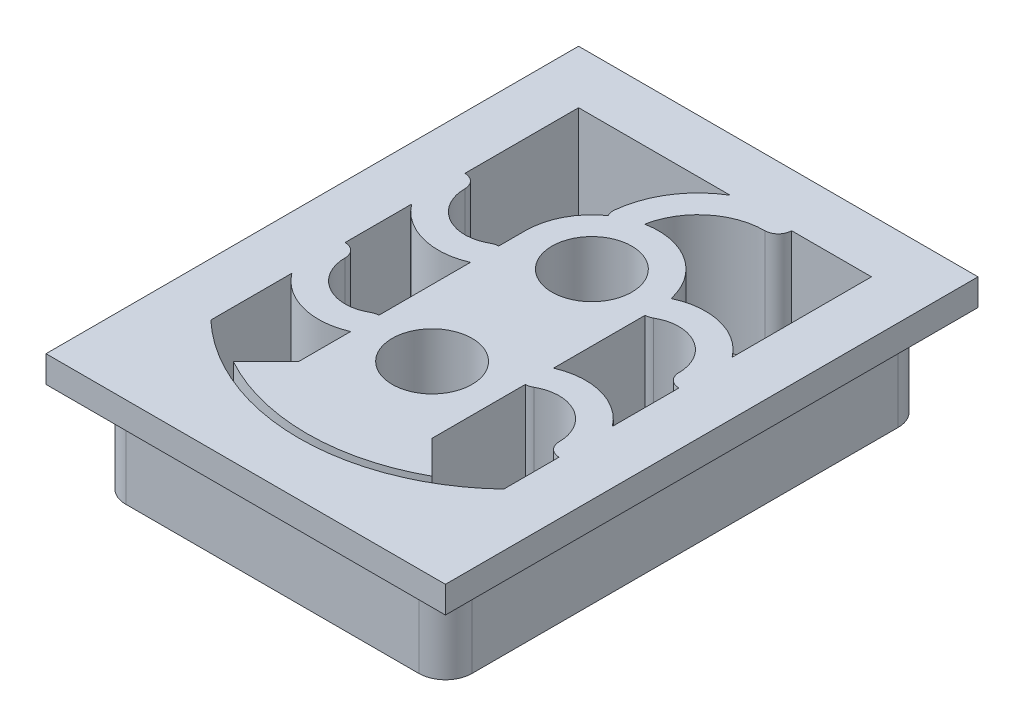
SolidWorks part; units mm, degrees
ref_plane "Front Plane" through (0, 0, 0) normal (0, 0, 1) x (1, 0, 0)
ref_plane "Top Plane" through (0, 0, 0) normal (0, 1, 0) x (1, 0, 0)
ref_plane "Right Plane" through (0, 0, 0) normal (1, 0, 0) x (0, 0, -1)
sketch "Sketch1" plane through (0, 0, 0) normal (0, 1, 0) x (1, 0, 0)
  line L1 (-6.5, -9) -> (6.5, -9)
  line L2 (-6.5, -9) -> (-6.5, 9)
  line L3 (-6.5, 9) -> (6.5, 9)
  line L4 (6.5, -9) -> (6.5, 9)
  line L5 (-6.5, -9) -> (6.5, 9) construction
  line L6 (-6.5, 9) -> (6.5, -9) construction
  point P0 (0, 0)
  dimension "D1" = 18
  dimension "D2" = 13
extrude "Boss-Extrude1" add sketch "Sketch1" along normal blind 3.4
sketch "Sketch2" plane through (0, 3.4, 0) normal (0, 1, 0) x (1, 0, 0)
  line L8 (7.5, -10) -> (7.5, 10)
  line L9 (7.5, 10) -> (-7.5, 10)
  line L10 (-7.5, 10) -> (-7.5, -10)
  line L11 (-7.5, -10) -> (7.5, -10)
  line L12 (7.5, -10) -> (7.5, 10)
  line L13 (7.5, 10) -> (-7.5, 10)
  line L14 (-7.5, 10) -> (-7.5, -10)
  line L15 (-7.5, -10) -> (7.5, -10)
  dimension "D1" = 1
extrude "Boss-Extrude2" add sketch "Sketch2" along normal blind 1
sketch "Sketch4" plane through (0, 0, 0) normal (0, -1, 0) x (1, 0, 0)
  line L0 (-3.734, 6.734) -> (-2.5, 5.5)
  line L1 (3.734, 6.734) -> (2.5, 5.5)
  line L4 (0, -3) -> (0, 3)
  line L6 (2.5, -5.5) -> (-2.5, -5.5)
  line L7 (2.5, -5.5) -> (2.5, 5.5)
  line L8 (5.5, -8) -> (5.5, 8)
  line L9 (5.5, 8) -> (-5.5, 8)
  line L10 (-5.5, 8) -> (-5.5, -8)
  line L11 (-5.5, -8) -> (5.5, -8)
  line L12 (5.5, -8) -> (5.5, 8)
  line L13 (5.5, 8) -> (-5.5, 8)
  line L14 (-5.5, 8) -> (-5.5, -8)
  line L15 (-5.5, -8) -> (5.5, -8)
  line L16 (2.5, 5.5) -> (-2.5, 5.5)
  line L17 (-2.5, -5.5) -> (-2.5, 5.5)
  line L18 (2.5, -5.5) -> (-2.5, 5.5) construction
  line L19 (2.5, 5.5) -> (-2.5, -5.5) construction
  circle A0 centre (0, 3) radius 1.5
  circle A1 centre (0, -3) radius 1.5
  circle A3 centre (0, -3) radius 2.5
  arc A4 (-2.5, 3) -> (-5.5, 1.2679) centre (-3.5, 1.2679) ccw
  arc A5 (2.5, 1.5) -> (5.5, 3.2321) centre (3.5, 3.2321) ccw
  arc A6 (2.5, -3) -> (5.5, -1.2679) centre (3.5, -1.2679) ccw
  arc A7 (-2.5, -1.5) -> (-5.5, -3.2321) centre (-3.5, -3.2321) ccw
  arc A9 (-1, -5.2913) -> (2, -8) centre (2, -4.9843) ccw
  arc A11 (3.734, 6.734) -> (-3.734, 6.734) centre (0, 0) ccw
  arc A12 (0, 8) -> (-5.5, 5.8095) centre (0, 0) ccw
  arc A13 (0, 8) -> (5.5, 5.8095) centre (0, 0) cw
  arc A14 (-2.25, -1.067) -> (-6, -3.2321) centre (-3.5, -3.2321) ccw
  arc A15 (-2.25, 3.433) -> (-6, 1.2679) centre (-3.5, 1.2679) ccw
  arc A16 (2.25, 1.067) -> (6, 3.2321) centre (3.5, 3.2321) ccw
  arc A17 (2.25, -3.433) -> (6, -1.2679) centre (3.5, -1.2679) ccw
  arc A18 (-2.75, -1.933) -> (-5, -3.2321) centre (-3.5, -3.2321) ccw
  arc A19 (-2.75, 2.567) -> (-5, 1.2679) centre (-3.5, 1.2679) ccw
  arc A20 (2.75, 1.933) -> (5, 3.2321) centre (3.5, 3.2321) ccw
  arc A21 (2.75, -2.567) -> (5, -1.2679) centre (3.5, -1.2679) ccw
  arc A22 (-2.25, -1.067) -> (-2.75, -1.933) centre (-2.5, -1.5) cw
  arc A23 (-6, -3.2321) -> (-5, -3.2321) centre (-5.5, -3.2321) ccw
  arc A24 (-2.25, 3.433) -> (-2.75, 2.567) centre (-2.5, 3) cw
  arc A25 (-6, 1.2679) -> (-5, 1.2679) centre (-5.5, 1.2679) ccw
  arc A26 (2.25, 1.067) -> (2.75, 1.933) centre (2.5, 1.5) cw
  arc A27 (6, 3.2321) -> (5, 3.2321) centre (5.5, 3.2321) ccw
  arc A28 (2.25, -3.433) -> (2.75, -2.567) centre (2.5, -3) cw
  arc A29 (6, -1.2679) -> (5, -1.2679) centre (5.5, -1.2679) ccw
  arc A31 (-1.4974, -5.3422) -> (2, -8.5) centre (2, -4.9843) ccw
  arc A33 (-0.5026, -5.2404) -> (2, -7.5) centre (2, -4.9843) ccw
  arc A36 (-1.4974, -5.3422) -> (-0.5026, -5.2404) centre (-1, -5.2913) cw
  arc A37 (2, -8.5) -> (2, -7.5) centre (2, -8) ccw
  point P3 (0, 0)
  point P5 (0, 0)
  dimension "D3" = 3
  dimension "D6" = 7.7
  dimension "D8" = 4.5
  dimension "D7" = 2
  dimension "D13" = 135
  dimension "D14" = 0.5
  dimension "D2" = 6
  dimension "D4" = 11
  dimension "D5" = 5
  dimension "D9" = 4.5
  dimension "D10" = 4.5
  dimension "D11" = 3.5
  dimension "D1" = 1
  dimension "D15" = 0.5
  dimension "D16" = 0.5
  dimension "D17" = 0.5
extrude "Cut-Extrude2" cut sketch "Sketch4" against normal through all
fillet "Fillet1" radius 1 4 edges at (-6.5, 1.7, -9) (6.5, 1.7, -9) (6.5, 1.7, 9) (-6.5, 1.7, 9)
mirror "Mirror2" [suppressed]
delete or keep bodies "Body-Delete/Keep 2" [suppressed] type keep bodies bodies 111
mirror "Mirror1" [suppressed]
delete or keep bodies "Body-Delete/Keep 1" [suppressed] type keep bodies bodies 104
